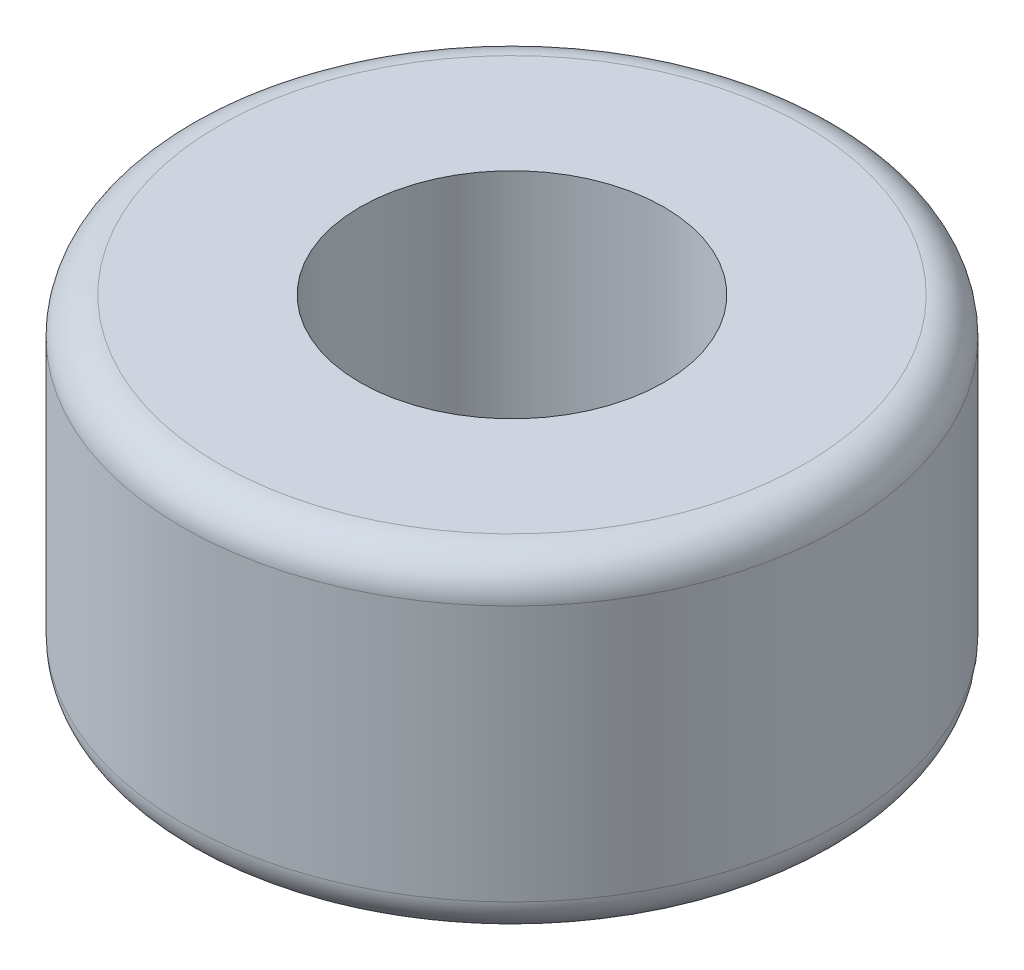
SolidWorks part; units mm, degrees
material "ABS"
ref_plane "Front" through (0, 0, 0) normal (0, 0, 1) x (1, 0, 0)
ref_plane "Top" through (0, 0, 0) normal (0, 1, 0) x (1, 0, 0)
ref_plane "Right" through (0, 0, 0) normal (1, 0, 0) x (0, 0, -1)
sketch "草图1" plane through (0, 0, 0) normal (0, 1, 0) x (1, 0, 0)
  circle A0 centre (0, 0) radius 4.15
  circle A1 centre (0, 0) radius 9
  dimension "D1" = 8.3
  dimension "D2" = 18
extrude "凸台-拉伸1" add sketch "草图1" along normal blind 9
fillet "圆角1" radius 1 2 edges at (0, 0, 9) (0, 9, 9)
